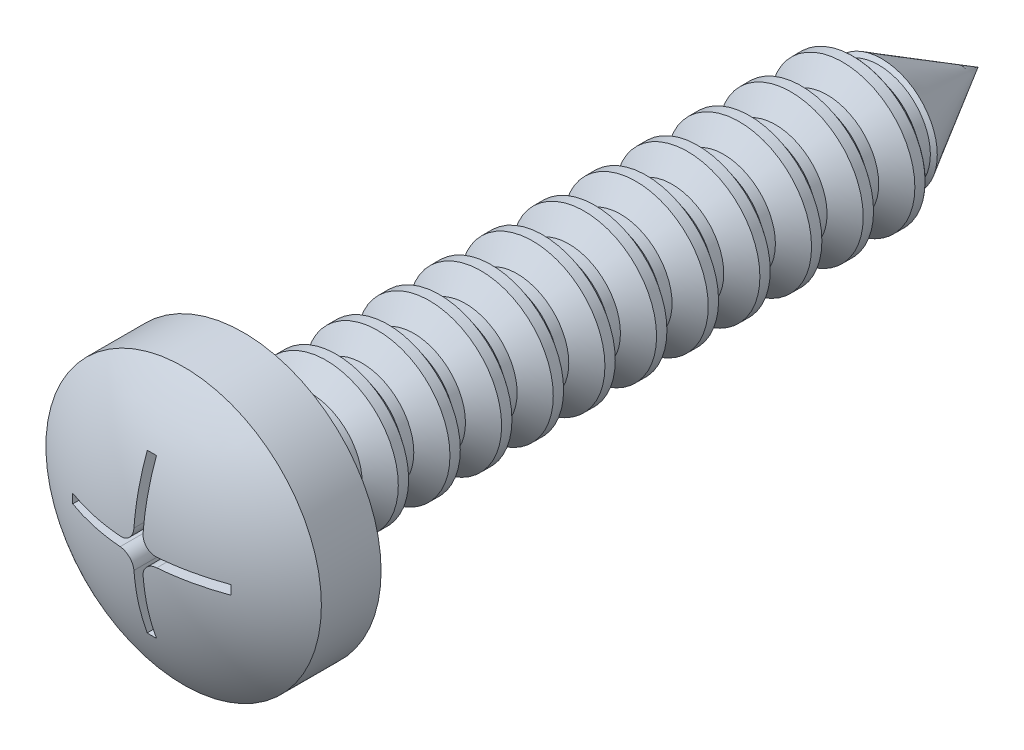
SolidWorks part; units mm, degrees
revolve "基体-旋转" add sketch "草图8" angle 360 about L0
sketch "草图8" plane through (0, 0, 0) normal (1, 0, 0) x (0, 0, -1)
  line L0 (-11.71, 0) -> (1.33, 0) construction
  line L1 (0, 0) -> (-36.6, 0)
  line L4 (-34.6, 6) -> (-32, 6)
  line L5 (-32, 6) -> (-32, 3.15)
  line L6 (-32, 3.15) -> (-5.456, 3.15)
  line L7 (-5.456, 3.15) -> (0, 0)
  arc A0 (-36.6, 0) -> (-34.6, 6) centre (-26.6, 0) cw
  dimension "D4" = 10
  dimension "D1" = 32
  dimension "D2" = 30
  dimension "D5" = 6.3
  dimension "D3" = 12
  dimension "D6" = 4.6
cosmetic thread "装饰螺纹线1" parameters "D1"=24.2, "D2"=5.4558
extrude "切除-拉伸2" cut sketch "草图7" against normal blind 3.6
sketch "草图7" plane through (0, 0, 36.6) normal (0, 0, 1) x (1, 0, 0)
  line L0 (-7.1, 0) -> (5.9, 0) construction
  line L1 (0, 7.5) -> (0, -7) construction
  line L2 (0.2, 3.4442) -> (0.2, 0.7975)
  line L3 (0, 0) -> (4.9858, 4.9858) construction
  line L4 (3.4442, 0.2) -> (0.7975, 0.2)
  line L5 (3.4442, -0.2) -> (0.7975, -0.2)
  line L6 (0.2, -3.4442) -> (0.2, -0.7975)
  line L7 (-0.2, -3.4442) -> (-0.2, -0.7975)
  line L8 (-3.4442, -0.2) -> (-0.7975, -0.2)
  line L9 (-3.4442, 0.2) -> (-0.7975, 0.2)
  line L10 (-0.2, 3.4442) -> (-0.2, 0.7975)
  line L11 (0, 0) -> (-4.9858, 4.9858) construction
  arc A0 (-0.2, 3.4442) -> (0.2, 3.4442) centre (0, 0) cw
  arc A1 (3.4442, -0.2) -> (3.4442, 0.2) centre (0, 0) ccw
  arc A2 (0.7975, 0.2) -> (0.2, 0.7975) centre (0.7975, 0.7975) cw
  arc A3 (-0.7975, 0.2) -> (-0.2, 0.7975) centre (-0.7975, 0.7975) ccw
  arc A4 (-0.2, -3.4442) -> (0.2, -3.4442) centre (0, 0) ccw
  arc A5 (0.7975, -0.2) -> (0.2, -0.7975) centre (0.7975, -0.7975) ccw
  arc A6 (-3.4442, -0.2) -> (-3.4442, 0.2) centre (0, 0) cw
  arc A7 (-0.7975, -0.2) -> (-0.2, -0.7975) centre (-0.7975, -0.7975) cw
  dimension "D10" = 3.45
  dimension "D1" = 0.5975
  dimension "D2" = 0.5975
ref_plane "前视" through (0, 0, 0) normal (0, 0, 1) x (1, 0, 0)
ref_plane "上视" through (0, 0, 0) normal (0, 1, 0) x (1, 0, 0)
ref_plane "右视" through (0, 0, 0) normal (1, 0, 0) x (0, 0, -1)
sketch "尺寸草图" plane through (0, 0, 0) normal (1, 0, 0) x (0, 0, -1)
  line L0 (-32, 12) -> (-32, 0)
  line L1 (-32, 0) -> (0, 0)
  line L2 (0, 0) -> (0, 6.3)
  point P4 (-27.4, 0)
  point P6 (0, 1.8)
  point P7 (-30.2, 0)
  point P8 (-32, 11.75)
  point P9 (-32, 2)
  point P10 (-6.9, 0)
  point P11 (-3.6, 0)
  point P12 (-30.02, 0)
  point P13 (-24.7, 0)
  point P14 (-26, 0)
  dimension "l" = 32
  dimension "E" = 12
  dimension "K" = 4.6
  dimension "d" = 6.3
  dimension "P" = 1.8
  dimension "A" = 1.8
  dimension "R" = 0.25
  dimension "Rf" = 10
  dimension "HM" = 6.9
  dimension "HH" = 3.6
  dimension "HE" = 1.98
  dimension "Da" = 7.3
  dimension "Yc" = 6
ref_plane "基准面6" through (0, 0, 36.6) normal (0, 0, 1) x (1, 0, 0)
sketch "草图9" plane through (0, 0, 0) normal (1, 0, 0) x (0, 0, -1)
  line L0 (-30.2, 3.15) -> (-28.4, 3.15)
  line L1 (-30.2, 3.15) -> (-29.525, 2.25)
  line L2 (-29.075, 2.25) -> (-29.525, 2.25)
  line L3 (-29.075, 2.25) -> (-28.4, 3.15)
  line L4 (-11.71, 0) -> (1.33, 0) construction
  line L5 (-32, -6) -> (-32, 6) construction
  line L6 (-6.912, 0) -> (-2.6011, 0) construction
  line L7 (-33, 0) -> (-35.986, 0) construction
  dimension "D1" = 1.8
  dimension "D2" = 0.45
  dimension "D3" = 0.9
  dimension "D4" = 3.15
  dimension "D5" = 1.8
revolve "切除-旋转1" cut sketch "草图9" angle 360 about L6
pattern_linear "阵列(线性)1" count 13 spacing 2.25 along (0, 0, -1) of "切除-旋转1"
fillet "圆角1" radius 0.25 1 edges at (3.15, 0, 32)
equation "\"D16@基准面6\" = \"l@尺寸草图\"+\"K@尺寸草图\""
equation "\"D1@草图8\" = \"l@尺寸草图\""
equation "\"D6@草图8\" = \"K@尺寸草图\""
equation "\"D5@草图8\" = \"d@尺寸草图\""
equation "\"D3@草图8\" = \"E@尺寸草图\""
equation "\"D4@草图8\" = \"Rf@尺寸草图\""
equation "\"D10@草图7\" = \"HM@尺寸草图\"/2"
equation "\"D1@切除-拉伸2\" = \"HH@尺寸草图\""
equation "\"D1@草图9\" = \"P@尺寸草图\""
equation "\"D2@草图9\" = \"D1@草图9\"/4"
equation "\"D3@草图9\" = \"D1@草图9\"/2"
equation "\"D4@草图9\" = \"d@尺寸草图\"/2"
equation "\"D5@草图9\" = \"A@尺寸草图\""
equation "\"D3@阵列(线性)1\" = \"A@尺寸草图\"*5/4"
equation "\"D1@阵列(线性)1\" = (\"l@尺寸草图\"-\"A@尺寸草图\")/\"D3@阵列(线性)1\""
equation "\"D2@装饰螺纹线1\" = \"d@尺寸草图\"*0.866"
equation "\"D1@装饰螺纹线1\" = \"l@尺寸草图\"-\"Yc@尺寸草图\"-\"A@尺寸草图\""
equation "\"D1@圆角1\" = \"R@尺寸草图\""
